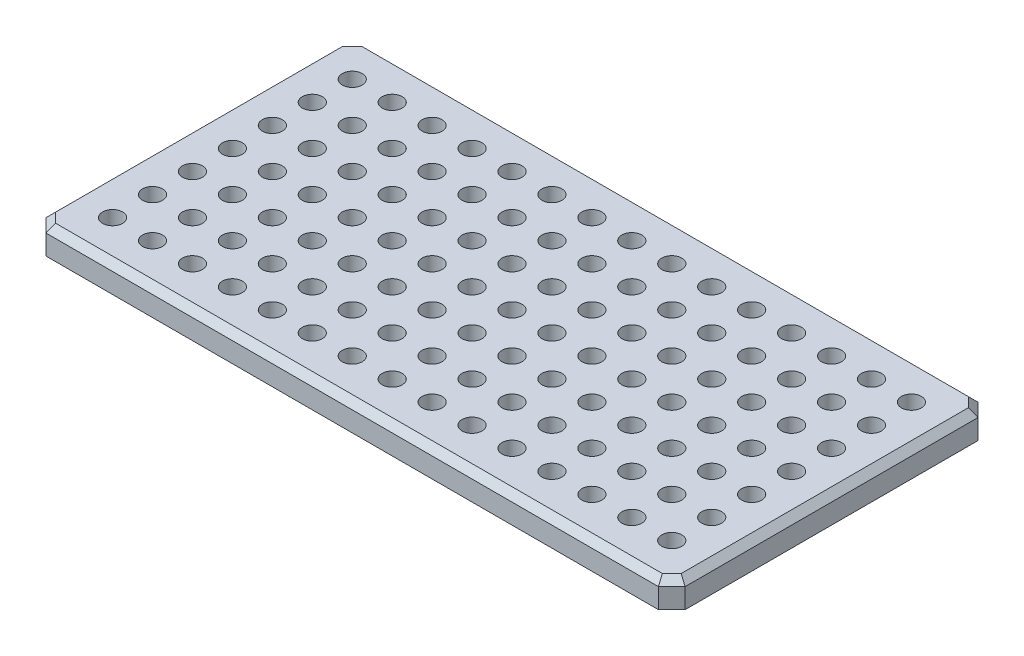
SolidWorks part; units mm, degrees
material "Plain Carbon Steel"
ref_plane "Front Plane" through (0, 0, 0) normal (0, 0, 1) x (1, 0, 0)
ref_plane "Top Plane" through (0, 0, 0) normal (0, 1, 0) x (1, 0, 0)
ref_plane "Right Plane" through (0, 0, 0) normal (1, 0, 0) x (0, 0, -1)
sketch "Sketch1" plane through (0, 0, 0) normal (0, 1, 0) x (1, 0, 0)
  line L1 (304.8, -152.4) -> (-304.8, -152.4)
  line L2 (304.8, -152.4) -> (304.8, 152.4)
  line L3 (304.8, 152.4) -> (-304.8, 152.4)
  line L4 (-304.8, -152.4) -> (-304.8, 152.4)
  line L5 (0, 152.4) -> (0, -152.4) construction
  line L6 (304.8, 0) -> (-304.8, 0) construction
  point P0 (0, 0)
  dimension "Hello" = 609.6
  dimension "How" = 304.8
extrude "Boss-Extrude1" add sketch "Sketch1" along normal blind 25.4
chamfer "Chamfer1" distance 12.7 angle 45 4 edges at (304.8, 12.7, 152.4) (304.8, 12.7, -152.4) (-304.8, 12.7, 152.4) (-304.8, 12.7, -152.4)
chamfer "Chamfer2" distance 6.35 angle 45 8 edges at (-298.45, 25.4, 146.05) (-304.8, 25.4, 0) (-298.45, 25.4, -146.05) (0, 25.4, -152.4) (298.45, 25.4, -146.05) (304.8, 25.4, 0) (298.45, 25.4, 146.05) (0, 25.4, 152.4)
sketch "Sketch2" plane through (0, 25.4, 0) normal (0, 1, 0) x (1, 0, 0)
  line L0 (-304.8, -139.7) -> (-304.8, 139.7) construction
  line L1 (-292.1, 152.4) -> (292.1, 152.4) construction
  circle A0 centre (-266.7, 114.3) radius 9.525
  dimension "D1" = 19.05
  dimension "D2" = 38.1
  dimension "D3" = 38.1
extrude "Cut-Extrude1" cut sketch "Sketch2" against normal through all
pattern_linear "LPattern1" count 15 spacing 38.1 along (1, 0, 0) count 7 spacing 38.1 along (0, 0, 1) of "Cut-Extrude1"
